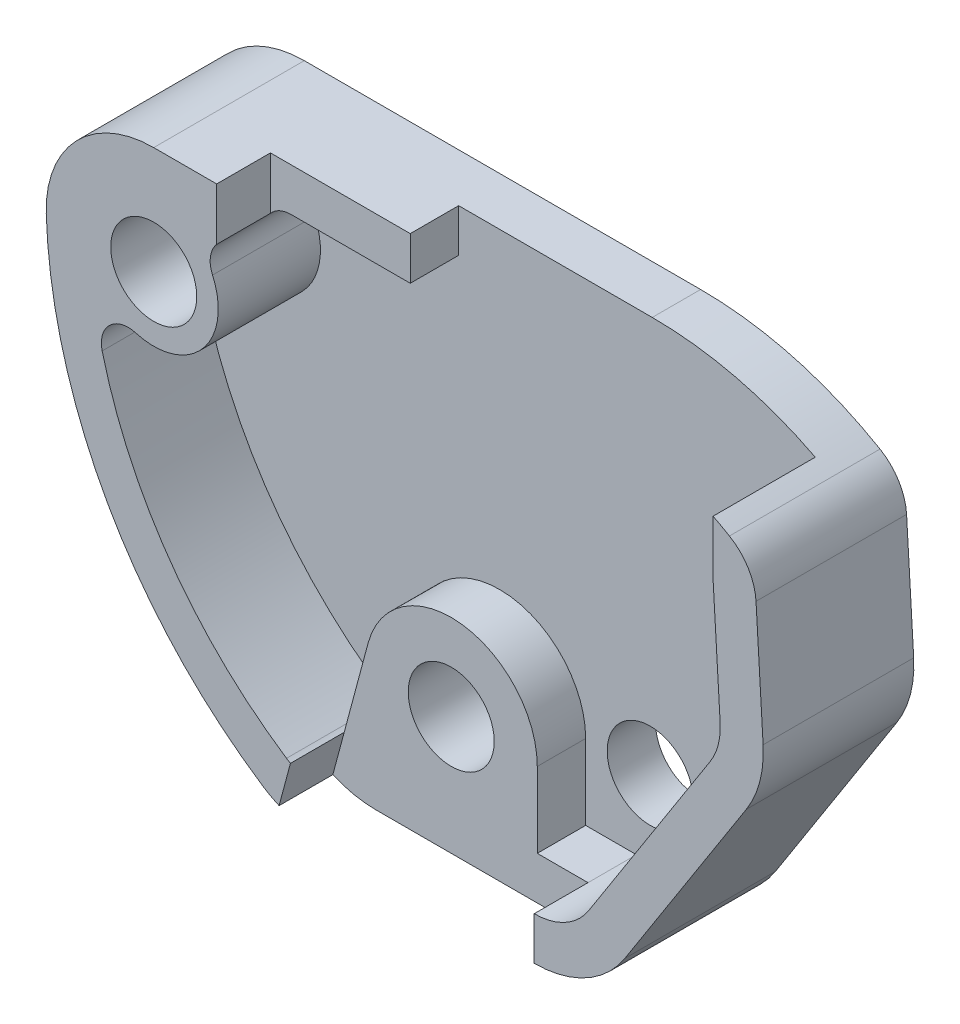
SolidWorks part; units mm, degrees
ref_plane "Plano frontal" through (0, 0, 0) normal (0, 0, 1) x (1, 0, 0)
ref_plane "Plano superior" through (0, 0, 0) normal (0, 1, 0) x (1, 0, 0)
ref_plane "Plano direito" through (0, 0, 0) normal (1, 0, 0) x (0, 0, -1)
sketch "Esboço1" plane through (0, 0, 0) normal (0, 0, 1) x (1, 0, 0)
  line L0 (9.1479, 0) -> (46, 0)
  line L1 (65.1492, -8.5363) -> (65.8093, -19.7578)
  line L2 (64.2493, -25.7355) -> (52.9501, -43.3905)
  line L3 (44.5273, -48) -> (24.8065, -48)
  arc A0 (46, 0) -> (62.6785, -4.5118) centre (46, -33.0833) cw
  arc A1 (-0.8464, -10.3382) -> (19.2861, -46.3382) centre (44.1279, -8.8164) ccw
  arc A2 (24.8065, -48) -> (19.2861, -46.3382) centre (24.8065, -38) cw
  arc A3 (52.9501, -43.3905) -> (44.5273, -48) centre (44.5273, -38) cw
  arc A4 (65.8093, -19.7578) -> (64.2493, -25.7355) centre (55.8265, -20.345) cw
  arc A5 (9.1479, 0) -> (-0.8464, -10.3382) centre (9.1479, -10) ccw
  arc A6 (62.6785, -4.5118) -> (65.1492, -8.5363) centre (60.1578, -8.8299) cw
  point P16 (22, -48)
  point P19 (50, -48)
  point P22 (66, -23)
  point P25 (0, 0)
  point P28 (65, -6)
  dimension "D1" = 46
  dimension "D9" = 45
  dimension "D10" = 10
  dimension "D11" = 5
  dimension "D2" = 66
  dimension "D3" = 65
  dimension "D4" = 48
  dimension "D5" = 42
  dimension "D6" = 25
  dimension "D7" = 16
  dimension "D8" = 28
extrude "Ressalto-extrusão1" add sketch "Esboço1" along normal blind 4.5
sketch "Esboço2" plane through (0, 0, 4.5) normal (0, 0, 1) x (1, 0, 0)
  line L0 (28, -4) -> (16.8939, -4)
  line L1 (39.8093, -44) -> (44.5273, -44)
  line L2 (49.581, -41.2343) -> (60.8802, -23.5793)
  line L3 (61.8162, -19.9927) -> (61.1561, -8.7712)
  line L4 (46, 0) -> (9.1479, 0)
  line L5 (24.8065, -48) -> (44.5273, -48)
  line L6 (52.9501, -43.3905) -> (64.2493, -25.7355)
  line L7 (65.8093, -19.7578) -> (65.1492, -8.5363)
  line L8 (28, 0) -> (9.1479, 0)
  line L9 (24.8065, -48) -> (44.5273, -48)
  line L10 (52.9501, -43.3905) -> (64.2493, -25.7355)
  line L11 (65.8093, -19.7578) -> (65.1492, -8.5363)
  line L12 (28, -4) -> (28, 0)
  line L13 (61.1561, -8.7712) -> (61.1561, -3.6759)
  line L14 (46, -4) -> (9.1479, -4) construction
  line L15 (46, 0) -> (9.1479, 0) construction
  line L16 (39.8093, -44) -> (39.8093, -37)
  line L17 (24.0819, -34.9294) -> (21.8553, -43.2392)
  line L19 (24.8065, -44) -> (44.5273, -44) construction
  arc A2 (4.3546, -18.7704) -> (21.4943, -43.0029) centre (44.1279, -8.8164) ccw
  arc A3 (21.4943, -43.0029) -> (21.8588, -43.226) centre (24.8065, -38) ccw
  arc A4 (44.5273, -44) -> (49.581, -41.2343) centre (44.5273, -38) ccw
  arc A5 (60.8802, -23.5793) -> (61.8162, -19.9927) centre (55.8265, -20.345) ccw
  arc A7 (62.6785, -4.5118) -> (46, 0) centre (46, -33.0833) ccw
  arc A8 (9.1479, 0) -> (-0.8464, -10.3382) centre (9.1479, -10) ccw
  arc A9 (-0.8464, -10.3382) -> (19.2861, -46.3382) centre (44.1279, -8.8164) ccw
  arc A10 (19.2861, -46.3382) -> (24.8065, -48) centre (24.8065, -38) ccw
  arc A11 (44.5273, -48) -> (52.9501, -43.3905) centre (44.5273, -38) ccw
  arc A12 (64.2493, -25.7355) -> (65.8093, -19.7578) centre (55.8265, -20.345) ccw
  arc A13 (65.1492, -8.5363) -> (62.6785, -4.5118) centre (60.1578, -8.8299) ccw
  arc A14 (62.6785, -4.5118) -> (61.1561, -3.6759) centre (46, -33.0833) ccw
  arc A15 (9.1479, 0) -> (-0.8464, -10.3382) centre (9.1479, -10) ccw
  arc A16 (-0.8464, -10.3382) -> (19.2861, -46.3382) centre (44.1279, -8.8164) ccw
  arc A17 (19.2861, -46.3382) -> (24.8065, -48) centre (24.8065, -38) ccw
  arc A18 (44.5273, -48) -> (52.9501, -43.3905) centre (44.5273, -38) ccw
  arc A19 (64.2493, -25.7355) -> (65.8093, -19.7578) centre (55.8265, -20.345) ccw
  arc A20 (65.1492, -8.5363) -> (62.6785, -4.5118) centre (60.1578, -8.8299) ccw
  arc A21 (7.4763, -15.7624) -> (14.6157, -7.5294) centre (9.1479, -10) ccw
  arc A22 (7.4763, -15.7624) -> (4.3546, -18.7704) centre (6.7798, -18.1634) ccw
  arc A23 (16.8939, -4) -> (14.6157, -7.5294) centre (16.8939, -6.5) ccw
  arc A24 (60.662, -7.9663) -> (46, -4) centre (46, -33.0833) ccw construction
  arc A25 (61.1561, -8.7712) -> (60.662, -7.9663) centre (60.1578, -8.8299) ccw construction
  arc A26 (39.8093, -37) -> (24.0819, -34.9294) centre (31.8093, -37) ccw
  arc A27 (62.6785, -4.5118) -> (46, 0) centre (46, -33.0833) ccw construction
  arc A29 (21.4943, -43.0029) -> (24.8065, -44) centre (24.8065, -38) ccw construction
  arc A30 (9.1479, -4) -> (3.1514, -10.2029) centre (9.1479, -10) ccw construction
  arc A31 (3.1514, -10.2029) -> (21.4943, -43.0029) centre (44.1279, -8.8164) ccw construction
  dimension "D3" = 5
  dimension "D4" = 28
  dimension "D5" = 8
  dimension "D9" = 6
  dimension "D6" = 26
  dimension "D7" = 11
  dimension "D8" = 15
  dimension "D1" = 0
  dimension "D2" = 4
extrude "Ressalto-extrusão2" add sketch "Esboço2" along normal blind 9.5
sketch "Esboço3" plane through (0, 0, 14) normal (0, 0, 1) x (1, 0, 0)
  circle A0 centre (31.8093, -37) radius 4
  arc A1 (39.8093, -37) -> (24.0819, -34.9294) centre (31.8093, -37) ccw construction
  circle A2 centre (45.8093, -37) radius 4
  dimension "D1" = 8
  dimension "D2" = 14
extrude "Corte-extrusão1" cut sketch "Esboço3" against normal through all
sketch "Esboço4" plane through (0, 0, 14) normal (0, 0, 1) x (1, 0, 0)
  circle A0 centre (9.1479, -10) radius 4
  dimension "D1" = 8
extrude "Corte-extrusão2" cut sketch "Esboço4" against normal blind 9
sketch "Esboço5" plane through (0, 0, 14) normal (0, 0, 1) x (1, 0, 0)
  line L2 (28, -4) -> (28, 0)
  line L3 (28, 0) -> (15, 0)
  line L4 (15, -4.8681) -> (15, 0)
  line L5 (28, 0) -> (9.1479, 0) construction
  line L6 (28, -4) -> (16.8939, -4) construction
  line L7 (28, -4) -> (16.8939, -4)
  line L8 (39.8093, -44) -> (44.5273, -44) construction
  line L9 (39.8093, -44) -> (39.8093, -37) construction
  line L10 (24.0819, -34.9294) -> (21.8588, -43.226) construction
  line L11 (39.8093, -44) -> (44.5273, -44)
  line L12 (39.8093, -44) -> (39.8093, -37)
  line L13 (24.0819, -34.9294) -> (21.8588, -43.226)
  line L14 (21.8588, -43.226) -> (20.8037, -47.1639)
  line L15 (24.8065, -48) -> (44.5273, -48) construction
  line L16 (24.8065, -48) -> (44.5273, -48)
  line L17 (44.5273, -44) -> (44.5273, -48)
  arc A0 (16.8939, -4) -> (14.6157, -7.5294) centre (16.8939, -6.5) ccw construction
  arc A1 (16.8939, -4) -> (15, -4.8681) centre (16.8939, -6.5) ccw
  arc A2 (39.8093, -37) -> (24.0819, -34.9294) centre (31.8093, -37) ccw construction
  arc A3 (39.8093, -37) -> (24.0819, -34.9294) centre (31.8093, -37) ccw
  arc A4 (19.2861, -46.3382) -> (24.8065, -48) centre (24.8065, -38) ccw construction
  arc A7 (20.8037, -47.1639) -> (24.8065, -48) centre (24.8065, -38) ccw
  dimension "D1" = 15
extrude "Corte-extrusão3" cut sketch "Esboço5" against normal blind 5
